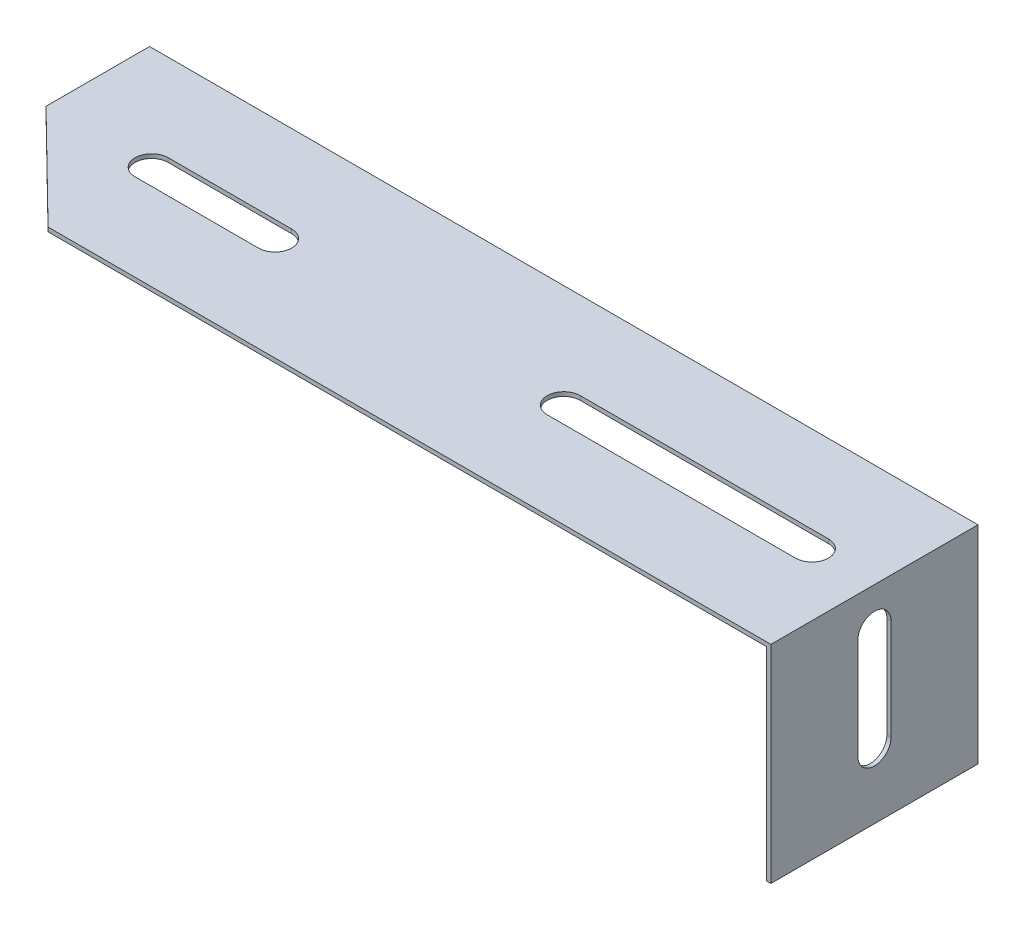
SolidWorks part; units mm, degrees
ref_plane "Front Plane" through (0, 0, 0) normal (0, 0, 1) x (1, 0, 0)
ref_plane "Top Plane" through (0, 0, 0) normal (0, 1, 0) x (1, 0, 0)
ref_plane "Right Plane" through (0, 0, 0) normal (1, 0, 0) x (0, 0, -1)
sketch "Sketch1" plane through (0, 0, 0) normal (0, 1, 0) x (1, 0, 0)
  line L0 (-174.5, 0) -> (-200, 25)
  line L1 (0, 0) -> (-200, 0)
  line L2 (0, 0) -> (0, 50)
  line L3 (0, 50) -> (-200, 50)
  line L4 (-200, 0) -> (-200, 50)
  line L5 (-174.5, 25) -> (-144.7, 25) construction
  line L6 (-174.5, 29) -> (-144.7, 29)
  line L7 (-174.5, 21) -> (-144.7, 21)
  line L8 (-75, 25) -> (-15.08, 25) construction
  line L9 (-75, 29) -> (-15.08, 29)
  line L10 (-75, 21) -> (-15.08, 21)
  arc A0 (-174.5, 29) -> (-174.5, 21) centre (-174.5, 25) ccw
  arc A1 (-144.7, 21) -> (-144.7, 29) centre (-144.7, 25) ccw
  arc A2 (-75, 29) -> (-75, 21) centre (-75, 25) ccw
  arc A3 (-15.08, 21) -> (-15.08, 29) centre (-15.08, 25) ccw
  point P9 (-159.6, 25)
  point P14 (-45.04, 25)
  dimension "D1" = 200
  dimension "D2" = 50
  dimension "D3" = 174.5
  dimension "D4" = 8
  dimension "D5" = 8
  dimension "D6" = 15.08
  dimension "D7" = 75
  dimension "D8" = 144.7
extrude "Boss-Extrude1" add sketch "Sketch1" along normal blind 1 contours L4 L0 L1 L2 L3 A3 L10 A2 L9 A1 L7 A0 L6
sketch "Sketch2" plane through (0, 0, 0) normal (1, 0, 0) x (0, 0, -1)
  line L1 (0, 1) -> (50, 1)
  line L2 (0, 1) -> (0, -49)
  line L3 (0, -49) -> (50, -49)
  line L4 (50, 1) -> (50, -49)
  dimension "D1" = 50
extrude "Boss-Extrude2" add sketch "Sketch2" against normal blind 1
sketch "Sketch3" plane through (0, 0, 0) normal (1, 0, 0) x (0, 0, -1)
  line L0 (25, -8.5894) -> (25, -32.9152) construction
  line L1 (29, -8.5894) -> (29, -32.9152)
  line L2 (21, -8.5894) -> (21, -32.9152)
  line L3 (0, 1) -> (0, -49) construction
  arc A0 (29, -8.5894) -> (21, -8.5894) centre (25, -8.5894) ccw
  arc A1 (21, -32.9152) -> (29, -32.9152) centre (25, -32.9152) ccw
  point P2 (25, -20.7523)
  dimension "D1" = 8
  dimension "D2" = 25
extrude "Cut-Extrude1" cut sketch "Sketch3" against normal blind 1
